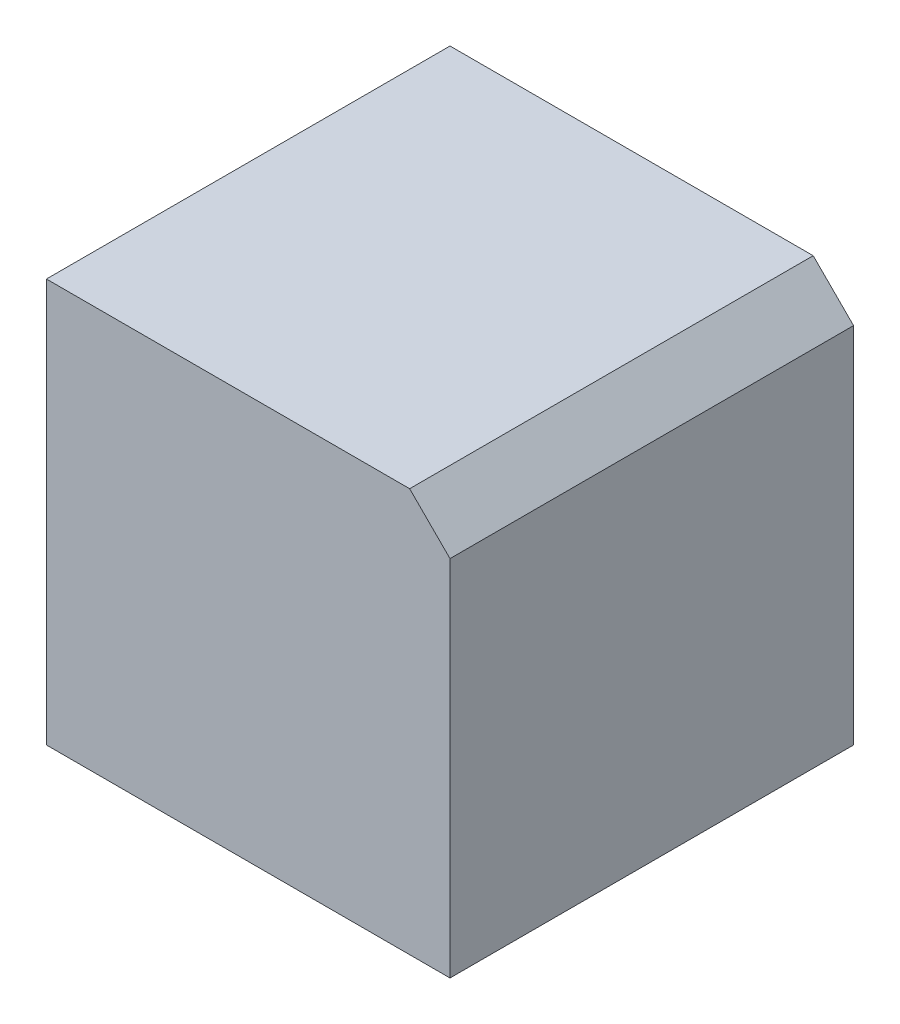
SolidWorks part; units mm, degrees
ref_plane "Front Plane" through (0, 0, 0) normal (0, 0, 1) x (1, 0, 0)
ref_plane "Top Plane" through (0, 0, 0) normal (0, 1, 0) x (1, 0, 0)
ref_plane "Right Plane" through (0, 0, 0) normal (1, 0, 0) x (0, 0, -1)
sketch "Sketch1" plane through (0, 0, 0) normal (0, 0, 1) x (1, 0, 0)
  line L1 (0, 0) -> (10, 0)
  line L2 (0, 0) -> (0, 10)
  line L3 (0, 10) -> (10, 10)
  line L4 (10, 0) -> (10, 10)
extrude "Boss-Extrude1" add sketch "Sketch1" along normal blind 10
chamfer "Chamfer1" distance 1 angle 45 1 edges at (10, 10, 5)
